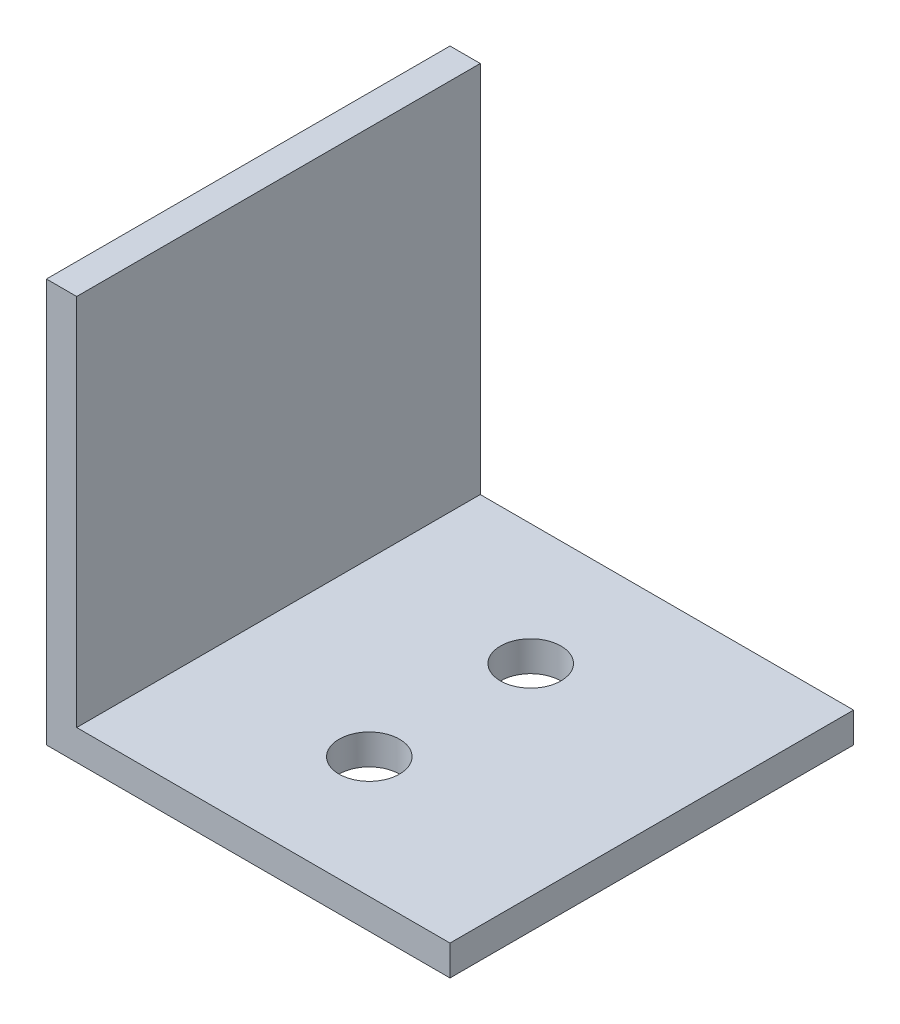
SolidWorks part; units mm, degrees
ref_plane "Plan de face" through (0, 0, 0) normal (0, 0, 1) x (1, 0, 0)
ref_plane "Plan de dessus" through (0, 0, 0) normal (0, 1, 0) x (1, 0, 0)
ref_plane "Plan de droite" through (0, 0, 0) normal (1, 0, 0) x (0, 0, -1)
sketch "Esquisse1" plane through (0, 0, 0) normal (0, 0, 1) x (1, 0, 0)
  line L0 (-18.7143, 3.4981) -> (-18.7143, -16.5019)
  line L1 (-18.7143, -16.5019) -> (1.2857, -16.5019)
  line L2 (1.2857, -16.5019) -> (1.2857, -15.0019)
  line L3 (1.2857, -15.0019) -> (-17.2143, -15.0019)
  line L4 (-17.2143, -15.0019) -> (-17.2143, 3.4981)
  line L5 (-17.2143, 3.4981) -> (-18.7143, 3.4981)
  dimension "D1" = 1.5
  dimension "D2" = 1.5
  dimension "D3" = 20
  dimension "D4" = 20
extrude "Extrusion1" add sketch "Esquisse1" along normal blind 20
sketch "Esquisse2" plane through (0, -15.0019, 0) normal (0, 1, 0) x (-1, 0, 0)
  line L0 (-1.2857, 20) -> (17.2143, 20) construction
  line L1 (-1.2857, 20) -> (-1.2857, 0) construction
  circle A0 centre (8.7143, 14) radius 1.5
  circle A1 centre (8.7143, 6) radius 1.5
  dimension "D1" = 8
  dimension "D2" = 6
  dimension "D3" = 10
  dimension "D4" = 10
extrude "Extrusion2" cut sketch "Esquisse2" against normal blind 20
